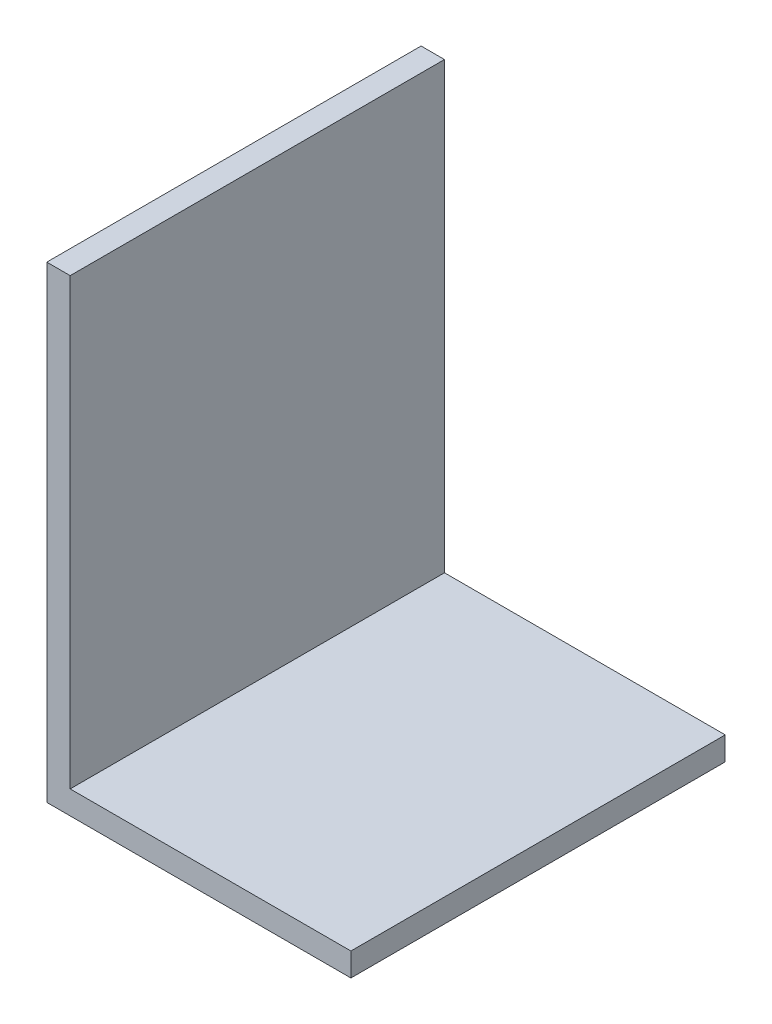
SolidWorks part; units mm, degrees
ref_plane "Front Plane" through (0, 0, 0) normal (0, 0, 1) x (1, 0, 0)
ref_plane "Top Plane" through (0, 0, 0) normal (0, 1, 0) x (1, 0, 0)
ref_plane "Right Plane" through (0, 0, 0) normal (1, 0, 0) x (0, 0, -1)
sketch "Sketch1" plane through (0, 0, 0) normal (0, 0, 1) x (1, 0, 0)
  line L0 (0, 0) -> (0, 19)
  line L1 (0, 0) -> (12, 0)
  dimension "D1" = 19
  dimension "D2" = 12
extrude "Extrude-Thin1" add sketch "Sketch1" along normal blind 16 thin thin type one direction wall 1
